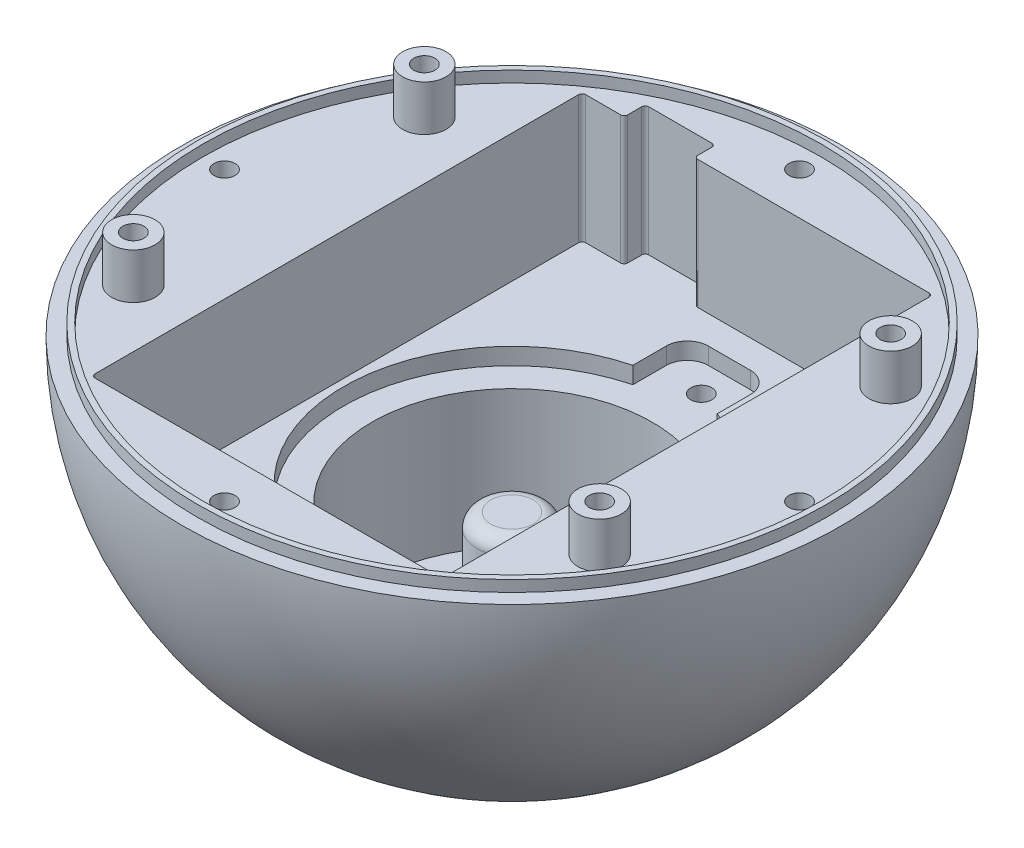
SolidWorks part; units mm, degrees
ref_plane "Front Plane" through (0, 0, 0) normal (0, 0, 1) x (1, 0, 0)
ref_plane "Top Plane" through (0, 0, 0) normal (0, 1, 0) x (1, 0, 0)
ref_plane "Right Plane" through (0, 0, 0) normal (1, 0, 0) x (0, 0, -1)
sketch "Sketch19" plane through (0, 22.1, 0) normal (0, 1, 0) x (1, 0, 0)
  line L0 (0, 47) -> (0, -47)
  arc A0 (0, 47) -> (0, -47) centre (0, 0) ccw
  dimension "D1" = 94
revolve "Shpere Hull" add sketch "Sketch19" angle 180 about L0
sketch "Sketch3" plane through (0, 22.1, 0) normal (0, 1, 0) x (1, 0, 0)
  line L1 (25, -35) -> (-25, -35)
  line L2 (25, -35) -> (25, 35)
  line L3 (25, 35) -> (-25, 35)
  line L4 (-25, -35) -> (-25, 35)
  line L5 (25, -35) -> (-25, 35) construction
  line L6 (25, 35) -> (-25, -35) construction
  point P0 (0, 0)
  dimension "D1" = 70
  dimension "D2" = 50
extrude "Battery Cavity" cut sketch "Sketch3" against normal blind 18.3
sketch "Sketch4" plane through (0, 22.1, 0) normal (0, 1, 0) x (1, 0, 0)
  line L0 (-40.5, 38) -> (40.5, 38) construction
  line L1 (-40.5, 40.5) -> (-40.5, -40.5) construction
  line L2 (40.5, -40.5) -> (40.5, 40.5) construction
  line L3 (40.5, 40.5) -> (-40.5, 40.5) construction
  line L4 (-20.75, 38) -> (20.75, 38) construction
  circle A0 centre (-20.75, 38) radius 1.5
  circle A1 centre (20.75, 38) radius 1.5
  point P12 (0, 38)
  dimension "D1" = 3
  dimension "D2" = 2.5
  dimension "D3" = 41.5
extrude "Cut-Extrude3" [suppressed] cut sketch "Sketch4" against normal blind 15
mirror "Mirror1" [suppressed] about plane through (0, 0, 0) normal (0, 0, 1)
sketch "Sketch7" plane through (0, 22.1, 0) normal (0, 1, 0) x (1, 0, 0)
  line L1 (33.25, -20.75) -> (-33.25, -20.75) construction
  line L2 (33.25, -20.75) -> (33.25, 20.75) construction
  line L3 (33.25, 20.75) -> (-33.25, 20.75) construction
  line L4 (-33.25, -20.75) -> (-33.25, 20.75) construction
  line L5 (33.25, -20.75) -> (-33.25, 20.75) construction
  line L6 (33.25, 20.75) -> (-33.25, -20.75) construction
  circle A0 centre (-33.25, 20.75) radius 1.5
  circle A1 centre (-33.25, -20.75) radius 1.5
  circle A2 centre (33.25, 20.75) radius 1.5
  circle A3 centre (33.25, -20.75) radius 1.5
  point P0 (0, 0)
  dimension "D3" = 3
  dimension "D1" = 41.5
  dimension "D2" = 66.5
extrude "Cut-Extrude4" cut sketch "Sketch7" against normal blind 12
sketch "Sketch8" plane through (0, 22.1, 0) normal (0, 1, 0) x (1, 0, 0)
  line L1 (38.75, -23.7) -> (-38.75, -23.7)
  line L2 (38.75, -23.7) -> (38.75, 23.7)
  line L3 (38.75, 23.7) -> (-38.75, 23.7)
  line L4 (-38.75, -23.7) -> (-38.75, 23.7)
  line L5 (38.75, -23.7) -> (-38.75, 23.7) construction
  line L6 (38.75, 23.7) -> (-38.75, -23.7) construction
  point P0 (0, 0)
  dimension "D1" = 47.4
  dimension "D2" = 77.5
sketch "Sketch9" plane through (0, 22.1, 0) normal (0, 1, 0) x (1, 0, 0)
  circle A0 centre (-33.25, 20.75) radius 3.1
  circle A1 centre (-33.25, 20.75) radius 1.5
  circle A2 centre (33.25, 20.75) radius 1.5
  circle A3 centre (33.25, 20.75) radius 3.1
  circle A4 centre (33.25, -20.75) radius 1.5
  circle A5 centre (33.25, -20.75) radius 3.1
  circle A6 centre (-33.25, -20.75) radius 1.5
  circle A7 centre (-33.25, -20.75) radius 3.1
  dimension "D1" = 1.6
extrude "PCB Stand Offs" add sketch "Sketch9" along normal blind 6.5
sketch "Sketch10" plane through (0, 22.1, 0) normal (0, 1, 0) x (1, 0, 0)
  line L0 (25, 35) -> (-25, 35) construction
  line L1 (-19, 35) -> (-9, 35)
  line L2 (-19, 35) -> (-19, 38)
  line L3 (-19, 38) -> (-9, 38)
  line L4 (-9, 35) -> (-9, 38)
  line L5 (-25, 35) -> (-25, -35) construction
  dimension "D1" = 3
  dimension "D2" = 10
  dimension "D3" = 6
extrude "Battery Cable" cut sketch "Sketch10" against normal up to surface (18.3 mm away) up to face at (0, 3.8, 0)
ref_plane "Plane1" through (0, 45.6, 0) normal (0, 1, 0) x (1, 0, 0)
ref_plane "Plane2" through (0, 30.6, 0) normal (0, -1, 0) x (-1, 0, 0)
sketch "Sketch16" [suppressed] plane through (0, 22.1, 0) normal (0, 1, 0) x (1, 0, 0)
  line L16 (-38.5, 26.5) -> (-38.5, -26.5)
  line L17 (-26.5, -38.5) -> (26.5, -38.5)
  line L18 (38.5, -26.5) -> (38.5, 26.5)
  line L19 (26.5, 38.5) -> (-26.5, 38.5)
  line L20 (-39.3, 26.5) -> (-39.3, -26.5)
  line L21 (-26.5, -39.3) -> (26.5, -39.3)
  line L22 (39.3, -26.5) -> (39.3, 26.5)
  line L23 (26.5, 39.3) -> (-26.5, 39.3)
  line L24 (-39.3, 26.5) -> (-39.3, -26.5)
  line L25 (-26.5, -39.3) -> (26.5, -39.3)
  line L26 (39.3, -26.5) -> (39.3, 26.5)
  line L27 (26.5, 39.3) -> (-26.5, 39.3)
  arc A20 (-26.5, 38.5) -> (-38.5, 26.5) centre (-26.5, 26.5) ccw
  arc A21 (-38.5, -26.5) -> (-26.5, -38.5) centre (-26.5, -26.5) ccw
  arc A22 (26.5, -38.5) -> (38.5, -26.5) centre (26.5, -26.5) ccw
  arc A23 (38.5, 26.5) -> (26.5, 38.5) centre (26.5, 26.5) ccw
  arc A24 (-39.3, -26.5) -> (-26.5, -39.3) centre (-26.5, -26.5) ccw
  arc A25 (26.5, -39.3) -> (39.3, -26.5) centre (26.5, -26.5) ccw
  arc A26 (39.3, 26.5) -> (26.5, 39.3) centre (26.5, 26.5) ccw
  arc A27 (-26.5, 39.3) -> (-39.3, 26.5) centre (-26.5, 26.5) ccw
  arc A28 (-39.3, -26.5) -> (-26.5, -39.3) centre (-26.5, -26.5) ccw
  arc A29 (26.5, -39.3) -> (39.3, -26.5) centre (26.5, -26.5) ccw
  arc A30 (39.3, 26.5) -> (26.5, 39.3) centre (26.5, 26.5) ccw
  arc A31 (-26.5, 39.3) -> (-39.3, 26.5) centre (-26.5, 26.5) ccw
  dimension "D1" = 1.2
  dimension "D2" = 0.8
extrude "Boss-Extrude4" [suppressed] add sketch "Sketch16" along normal blind 4
sketch "Sketch20" plane through (0, 22.1, 0) normal (0, 1, 0) x (1, 0, 0)
  circle A0 centre (0, 0) radius 44.9
  circle A1 centre (0, 0) radius 44.1
  circle A2 centre (0, 0) radius 46.5 construction
  dimension "D1" = 1.6
  dimension "D2" = 0.8
extrude "Raised Lip" add sketch "Sketch20" along normal blind 1.6
sketch "Sketch21" plane through (0, 28.6, 0) normal (0, 1, 0) x (1, 0, 0)
  line L1 (36.25, -23.5) -> (-36.25, -23.5)
  line L2 (36.25, -23.5) -> (36.25, 23.5)
  line L3 (36.25, 23.5) -> (-36.25, 23.5)
  line L4 (-36.25, -23.5) -> (-36.25, 23.5)
  line L5 (36.25, -23.5) -> (-36.25, 23.5) construction
  line L6 (36.25, 23.5) -> (-36.25, -23.5) construction
  circle A0 centre (0, 0) radius 43.2008
  point P0 (0, 0)
  dimension "D1" = 47
  dimension "D2" = 72.5
sketch "Sketch22" plane through (0, 3.8, 0) normal (0, 1, 0) x (1, 0, 0)
  circle A0 centre (0, 0) radius 20
  dimension "D1" = 40
extrude "Ballast Area" cut sketch "Sketch22" against normal blind 22 contours A0
fillet "Fillet2" radius 0.5 8 edges at (-25, 12.95, -35) (-19, 12.95, -35) (-19, 12.95, -38) (-9, 12.95, -38) (-9, 12.95, -35) (25, 12.95, 35) (-25, 12.95, 35) (25, 12.95, -35)
sketch "Sketch23" plane through (0, 22.1, 0) normal (0, 1, 0) x (1, 0, 0)
  circle A0 centre (0, 0) radius 41 construction
  circle A1 centre (0, 41) radius 1.5
  circle A2 centre (-33.25, 20.75) radius 1.5 construction
  circle A3 centre (0, -41) radius 1.5
  dimension "D1" = 82
extrude "Threaded Holes" cut sketch "Sketch23" against normal blind 10
pattern_circular "CirPattern1" count 4 over 360 about axis through (0, 0, 0) along (0, 1, 0) of "Threaded Holes"
ref_plane "Plane3" through (-36.25, 28.6, 23.5) normal (-0.8391, 0, 0.544) x (0.544, 0, 0.8391)
sketch "Sketch24" plane through (0, 3.8, 0) normal (0, 1, 0) x (1, 0, 0)
  line L1 (3, -31) -> (-3, -31)
  line L2 (6, -28) -> (6, 28)
  line L3 (3, 31) -> (-3, 31)
  line L4 (-6, -28) -> (-6, 28)
  line L5 (6, -31) -> (-6, 31) construction
  line L6 (6, 31) -> (-6, -31) construction
  circle A0 centre (0, 0) radius 24
  arc A1 (3, -31) -> (6, -28) centre (3, -28) ccw
  arc A2 (-3, -31) -> (-6, -28) centre (-3, -28) cw
  arc A3 (6, 28) -> (3, 31) centre (3, 28) ccw
  arc A4 (-3, 31) -> (-6, 28) centre (-3, 28) ccw
  dimension "D1" = 48
  dimension "D4" = 3
  dimension "D2" = 12
  dimension "D3" = 62
extrude "Cut-Extrude5" cut sketch "Sketch24" against normal blind 2.4 contours A0 | L4 A4 L3 A3 L2 A1 L1 A2
sketch "Sketch25" plane through (0, 1.4, 0) normal (0, 1, 0) x (1, 0, 0)
  circle A0 centre (0, 0) radius 27 construction
  circle A1 centre (0, 27) radius 1.5
  circle A2 centre (0, -27) radius 1.5
  circle A3 centre (-33.25, 20.75) radius 1.5 construction
  dimension "D1" = 54
extrude "Cut-Extrude6" cut sketch "Sketch25" against normal blind 10
sketch "Sketch26" plane through (0, -18.2, 0) normal (0, 1, 0) x (1, 0, 0)
  circle A0 centre (0, 0) radius 5
  dimension "D1" = 10
extrude "Boss-Extrude5" add sketch "Sketch26" along normal blind 18.5
fillet "Fillet3" radius 2 1 edges at (0, 0.3, 5)
equation "\"D2@Sketch2\"=\"D1@Sketch2\"/2+1.6"
equation "\"D3@Sketch2\"=\"D2@Sketch2\""
